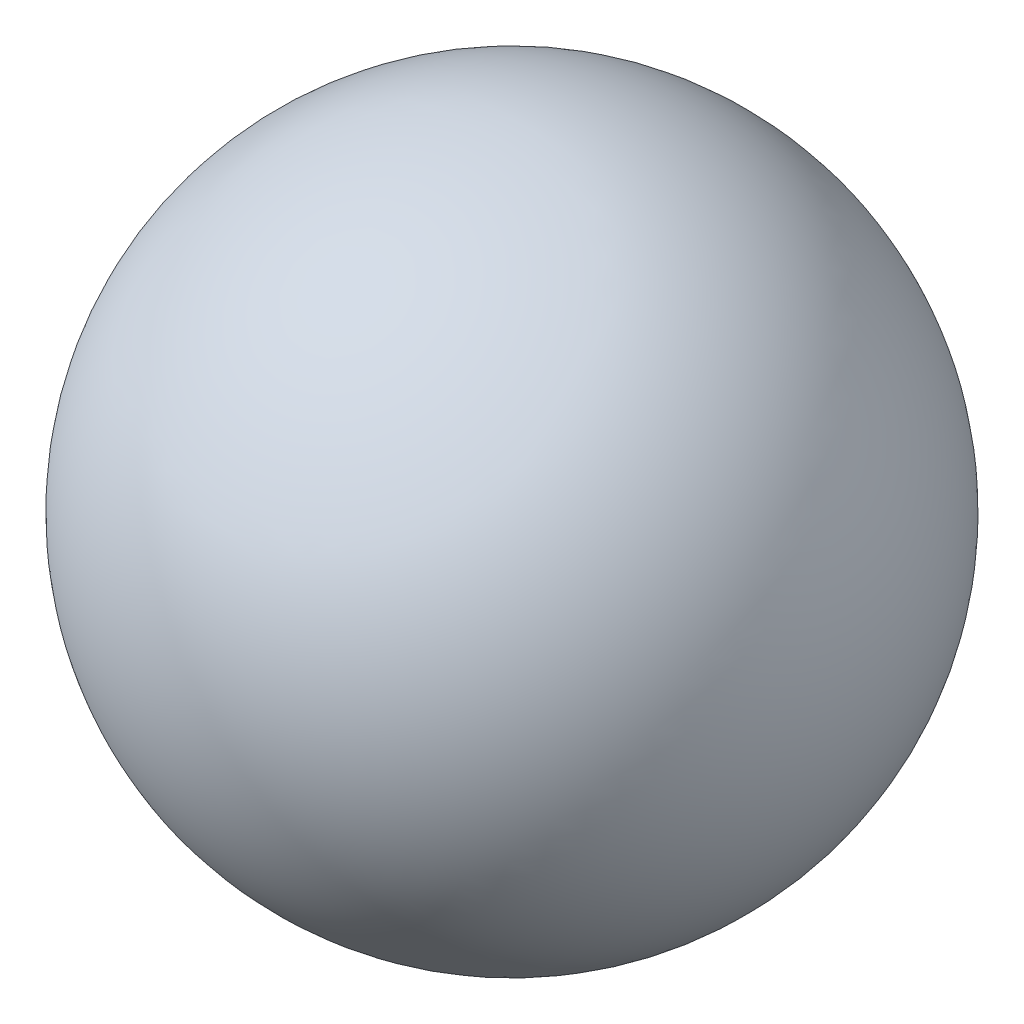
SolidWorks part; units mm, degrees
ref_plane "前视基准面" through (0, 0, 0) normal (0, 0, 1) x (1, 0, 0)
ref_plane "上视基准面" through (0, 0, 0) normal (0, 1, 0) x (1, 0, 0)
ref_plane "右视基准面" through (0, 0, 0) normal (1, 0, 0) x (0, 0, -1)
sketch "草图1" plane through (0, 0, 0) normal (0, 1, 0) x (1, 0, 0)
  line L0 (0, 11.038) -> (0, -10.3056)
  circle A0 centre (0, 0) radius 8.5
  dimension "D1" = 17
  dimension "D2" = 21.3437
revolve "旋转2" add sketch "草图1" angle 360 about L0
